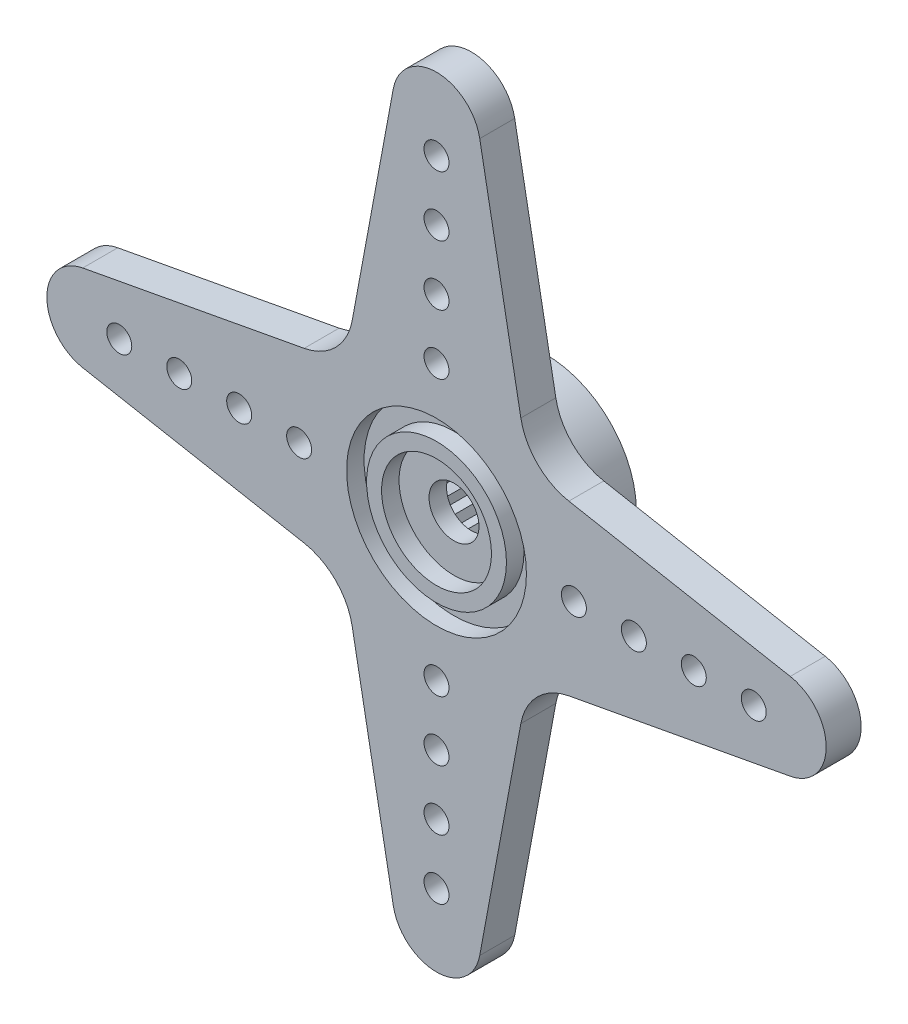
SolidWorks part; units mm, degrees
ref_plane "Front Plane" through (0, 0, 0) normal (0, 0, 1) x (1, 0, 0)
ref_plane "Top Plane" through (0, 0, 0) normal (0, 1, 0) x (1, 0, 0)
ref_plane "Right Plane" through (0, 0, 0) normal (1, 0, 0) x (0, 0, -1)
sketch "Sketch1" plane through (0, 0, 0) normal (0, 0, 1) x (1, 0, 0)
  line L50 (-10.25, 3) -> (-10.5946, 2.7283)
  line L51 (-10.5946, 2.7283) -> (-10.996, 2.9057)
  line L52 (-10.996, 2.9057) -> (-11.2623, 2.5569)
  line L53 (-11.2623, 2.5569) -> (-11.6952, 2.6289)
  line L54 (-11.6952, 2.6289) -> (-11.8664, 2.2248)
  line L55 (-11.8664, 2.2248) -> (-12.3036, 2.1869)
  line L56 (-12.3036, 2.1869) -> (-12.3689, 1.7529)
  line L57 (-12.3689, 1.7529) -> (-12.7829, 1.6075)
  line L58 (-12.7829, 1.6075) -> (-12.7382, 1.1709)
  line L59 (-12.7382, 1.1709) -> (-13.1031, 0.927)
  line L60 (-13.1031, 0.927) -> (-12.9512, 0.5153)
  line L61 (-12.9512, 0.5153) -> (-13.244, 0.1884)
  line L62 (-13.244, 0.1884) -> (-12.9945, -0.1727)
  line L63 (-12.9945, -0.1727) -> (-13.1968, -0.5621)
  line L64 (-13.1968, -0.5621) -> (-12.8654, -0.8498)
  line L65 (-12.8654, -0.8498) -> (-12.9644, -1.2773)
  line L66 (-12.9644, -1.2773) -> (-12.5719, -1.4735)
  line L67 (-12.5719, -1.4735) -> (-12.5615, -1.9123)
  line L68 (-12.5615, -1.9123) -> (-12.1325, -2.0047)
  line L69 (-12.1325, -2.0047) -> (-12.0133, -2.427)
  line L70 (-12.0133, -2.427) -> (-11.5748, -2.4098)
  line L71 (-11.5748, -2.4098) -> (-11.3543, -2.7893)
  line L72 (-11.3543, -2.7893) -> (-10.9339, -2.6636)
  line L73 (-10.9339, -2.6636) -> (-10.626, -2.9763)
  line L74 (-10.626, -2.9763) -> (-10.25, -2.75)
  line L75 (-10.25, -2.75) -> (-9.874, -2.9763)
  line L76 (-9.874, -2.9763) -> (-9.5661, -2.6636)
  line L77 (-9.5661, -2.6636) -> (-9.1456, -2.7893)
  line L78 (-9.1456, -2.7893) -> (-8.9251, -2.4098)
  line L79 (-8.9251, -2.4098) -> (-8.4866, -2.427)
  line L80 (-8.4866, -2.427) -> (-8.3675, -2.0047)
  line L81 (-8.3675, -2.0047) -> (-7.9384, -1.9123)
  line L82 (-7.9384, -1.9123) -> (-7.9281, -1.4735)
  line L83 (-7.9281, -1.4735) -> (-7.5355, -1.2773)
  line L84 (-7.5355, -1.2773) -> (-7.6346, -0.8498)
  line L85 (-7.6346, -0.8498) -> (-7.3031, -0.5621)
  line L86 (-7.3031, -0.5621) -> (-7.5054, -0.1727)
  line L87 (-7.5054, -0.1727) -> (-7.2559, 0.1884)
  line L88 (-7.2559, 0.1884) -> (-7.5487, 0.5153)
  line L89 (-7.5487, 0.5153) -> (-7.3968, 0.927)
  line L90 (-7.3968, 0.927) -> (-7.7617, 1.1709)
  line L91 (-7.7617, 1.1709) -> (-7.717, 1.6075)
  line L92 (-7.717, 1.6075) -> (-8.1311, 1.7529)
  line L93 (-8.1311, 1.7529) -> (-8.1963, 2.1869)
  line L94 (-8.1963, 2.1869) -> (-8.6336, 2.2248)
  line L95 (-8.6336, 2.2248) -> (-8.8047, 2.6289)
  line L96 (-8.8047, 2.6289) -> (-9.2376, 2.5569)
  line L97 (-9.2376, 2.5569) -> (-9.5039, 2.9057)
  line L98 (-9.5039, 2.9057) -> (-9.9053, 2.7283)
  line L99 (-9.9053, 2.7283) -> (-10.25, 3)
  line L100 (-10.25, 3) -> (-10.5946, 2.7283)
  line L101 (-10.5946, 2.7283) -> (-10.996, 2.9057)
  line L102 (-10.996, 2.9057) -> (-11.2623, 2.5569)
  line L103 (-11.2623, 2.5569) -> (-11.6952, 2.6289)
  line L104 (-11.6952, 2.6289) -> (-11.8664, 2.2248)
  line L105 (-11.8664, 2.2248) -> (-12.3036, 2.1869)
  line L106 (-12.3036, 2.1869) -> (-12.3689, 1.7529)
  line L107 (-12.3689, 1.7529) -> (-12.7829, 1.6075)
  line L108 (-12.7829, 1.6075) -> (-12.7382, 1.1709)
  line L109 (-12.7382, 1.1709) -> (-13.1031, 0.927)
  line L110 (-13.1031, 0.927) -> (-12.9512, 0.5153)
  line L111 (-12.9512, 0.5153) -> (-13.244, 0.1884)
  line L112 (-13.244, 0.1884) -> (-12.9945, -0.1727)
  line L113 (-12.9945, -0.1727) -> (-13.1968, -0.5621)
  line L114 (-13.1968, -0.5621) -> (-12.8654, -0.8498)
  line L115 (-12.8654, -0.8498) -> (-12.9644, -1.2773)
  line L116 (-12.9644, -1.2773) -> (-12.5719, -1.4735)
  line L117 (-12.5719, -1.4735) -> (-12.5615, -1.9123)
  line L118 (-12.5615, -1.9123) -> (-12.1325, -2.0047)
  line L119 (-12.1325, -2.0047) -> (-12.0133, -2.427)
  line L120 (-12.0133, -2.427) -> (-11.5748, -2.4098)
  line L121 (-11.5748, -2.4098) -> (-11.3543, -2.7893)
  line L122 (-11.3543, -2.7893) -> (-10.9339, -2.6636)
  line L123 (-10.9339, -2.6636) -> (-10.626, -2.9763)
  line L124 (-10.626, -2.9763) -> (-10.25, -2.75)
  line L125 (-10.25, -2.75) -> (-9.874, -2.9763)
  line L126 (-9.874, -2.9763) -> (-9.5661, -2.6636)
  line L127 (-9.5661, -2.6636) -> (-9.1456, -2.7893)
  line L128 (-9.1456, -2.7893) -> (-8.9251, -2.4098)
  line L129 (-8.9251, -2.4098) -> (-8.4866, -2.427)
  line L130 (-8.4866, -2.427) -> (-8.3675, -2.0047)
  line L131 (-8.3675, -2.0047) -> (-7.9384, -1.9123)
  line L132 (-7.9384, -1.9123) -> (-7.9281, -1.4735)
  line L133 (-7.9281, -1.4735) -> (-7.5355, -1.2773)
  line L134 (-7.5355, -1.2773) -> (-7.6346, -0.8498)
  line L135 (-7.6346, -0.8498) -> (-7.3031, -0.5621)
  line L136 (-7.3031, -0.5621) -> (-7.5054, -0.1727)
  line L137 (-7.5054, -0.1727) -> (-7.2559, 0.1884)
  line L138 (-7.2559, 0.1884) -> (-7.5487, 0.5153)
  line L139 (-7.5487, 0.5153) -> (-7.3968, 0.927)
  line L140 (-7.3968, 0.927) -> (-7.7617, 1.1709)
  line L141 (-7.7617, 1.1709) -> (-7.717, 1.6075)
  line L142 (-7.717, 1.6075) -> (-8.1311, 1.7529)
  line L143 (-8.1311, 1.7529) -> (-8.1963, 2.1869)
  line L144 (-8.1963, 2.1869) -> (-8.6336, 2.2248)
  line L145 (-8.6336, 2.2248) -> (-8.8047, 2.6289)
  line L146 (-8.8047, 2.6289) -> (-9.2376, 2.5569)
  line L147 (-9.2376, 2.5569) -> (-9.5039, 2.9057)
  line L148 (-9.5039, 2.9057) -> (-9.9053, 2.7283)
  line L149 (-9.9053, 2.7283) -> (-10.25, 3)
  circle A0 centre (-10.25, 0) radius 4.5
  dimension "D2" = 9
  dimension "D1" = 0
extrude "Boss-Extrude1" add sketch "Sketch1" against normal blind 3.75 contours A0 L149 L148 L147 L146 L145 L144 L143 L142 L141 L140 L139 L138 L137 L136 L135 L134 L133 L132 L131 L130 L129 L128 L127 L126 L125 L124 L123 L122 L121 L120 L119 L118 L117 L116 L115 L114 L113 L112 L111 L110 L109 L108 L107 L106 L105 L104 L103 L102 L101
sketch "Sketch2" plane through (0, 0, 0) normal (0, 0, 1) x (1, 0, 0)
  circle A0 centre (-10.25, 0) radius 1.25
  circle A1 centre (-10.25, 0) radius 3.5
  circle A2 centre (-10.25, 0) radius 4.5
  dimension "D1" = 7
  dimension "D2" = 2.5
  dimension "D3" = 9
extrude "Boss-Extrude2" add sketch "Sketch2" along normal blind 1.75 contours A2 A1 | A1 A0
sketch "Sketch4" plane through (0, 0, 1.75) normal (0, 0, 1) x (1, 0, 0)
  circle A0 centre (-10.25, 0) radius 3.5
  circle A1 centre (-10.25, 0) radius 2.75
  circle M2 centre (-10.25, 0) radius 1.25
  dimension "D1" = 7
  dimension "D2" = 0.75
extrude "Cut-Extrude1" cut sketch "Sketch4" against normal blind 0.875 contours A1 M2
sketch "Sketch6" plane through (0, 0, 1.75) normal (0, 0, 1) x (1, 0, 0)
  circle A0 centre (-10.25, 0) radius 3.5
  circle A1 centre (-10.25, 0) radius 2.75 construction
  circle A2 centre (-10.25, 0) radius 4.5
  circle M2 centre (-10.25, 0) radius 4.5
  dimension "D1" = 0.75
  dimension "D2" = 9
extrude "Cut-Extrude2" cut sketch "Sketch6" against normal blind 0.875 contours A0 M2
sketch "Sketch7" [suppressed] plane through (0, 0, 1.75) normal (0, 0, 1) x (1, 0, 0)
  circle A0 centre (-10.25, 0) radius 10.5
  circle A1 centre (-10.25, 0) radius 4.5
  dimension "D1" = 21
extrude "Boss-Extrude3" [suppressed] add sketch "Sketch7" against normal blind 1.75
sketch "Sketch9" [suppressed] plane through (0, 0, 1.75) normal (0, 0, 1) x (1, 0, 0)
  line L0 (-10.25, 0) -> (-10.25, 11.6833) construction
  circle A0 centre (-10.25, 7.875) radius 0.625
  circle A1 centre (-14.125, 7.875) radius 0.625
  circle A2 centre (-10.25, 0) radius 10.5 construction
  circle A3 centre (-6.375, 7.875) radius 0.625
  dimension "D1" = 2
  dimension "D2" = 1.25
  dimension "D3" = 1.25
  dimension "D4" = 2.625
extrude "Cut-Extrude3" [suppressed] cut sketch "Sketch9" against normal through all
pattern_circular "CirPattern1" [suppressed] count 4 over 360
chamfer "Chamfer1" [suppressed] distance 1 angle 30
sketch "Sketch10" plane through (0, 0, 1.75) normal (0, 0, 1) x (1, 0, 0)
  line L0 (-10.25, 0) -> (-10.25, 9.0053) construction
  line L1 (-10.25, 0) -> (0.0732, 10.3232) construction
  line L2 (-10.25, 0) -> (1.1009, 0) construction
  line L3 (-8.0869, 17.7016) -> (-6.0299, 6.622)
  line L4 (-3.6279, 4.2201) -> (7.4516, 2.163)
  line L5 (7.4516, -2.163) -> (-3.6279, -4.2201)
  line L6 (-6.0299, -6.622) -> (-8.0869, -17.7016)
  line L7 (-12.413, -17.7016) -> (-14.47, -6.622)
  line L8 (-16.872, -4.2201) -> (-27.9515, -2.163)
  line L9 (-27.9515, 2.163) -> (-16.872, 4.2201)
  line L10 (-14.47, 6.622) -> (-12.413, 17.7016)
  arc A0 (-8.0869, 17.7016) -> (-10.25, 19.5) centre (-10.25, 17.3) ccw
  arc A1 (7.4516, -2.163) -> (7.4516, 2.163) centre (7.05, 0) ccw
  arc A2 (-6.0299, 6.622) -> (-3.6279, 4.2201) centre (-3.0803, 7.1697) ccw
  circle A3 centre (-10.25, 15.875) radius 0.625
  circle A4 centre (-10.25, 12.875) radius 0.625
  circle A5 centre (-10.25, 9.875) radius 0.625
  circle A6 centre (-10.25, 6.875) radius 0.625
  arc A7 (7.4516, -2.163) -> (9.25, 0) centre (7.05, 0) ccw
  circle A8 centre (5.625, 0) radius 0.625
  circle A9 centre (2.625, 0) radius 0.625
  circle A10 centre (-0.375, 0) radius 0.625
  circle A11 centre (-3.375, 0) radius 0.625
  arc A12 (-3.6279, -4.2201) -> (-6.0299, -6.622) centre (-3.0803, -7.1697) ccw
  arc A13 (-12.413, -17.7016) -> (-8.0869, -17.7016) centre (-10.25, -17.3) ccw
  arc A14 (-12.413, -17.7016) -> (-10.25, -19.5) centre (-10.25, -17.3) ccw
  circle A15 centre (-10.25, -15.875) radius 0.625
  circle A16 centre (-10.25, -12.875) radius 0.625
  circle A17 centre (-10.25, -9.875) radius 0.625
  circle A18 centre (-10.25, -6.875) radius 0.625
  arc A19 (-14.47, -6.622) -> (-16.872, -4.2201) centre (-17.4196, -7.1697) ccw
  arc A20 (-27.9515, 2.163) -> (-27.9515, -2.163) centre (-27.5499, 0) ccw
  arc A21 (-27.9515, 2.163) -> (-29.7499, 0) centre (-27.5499, 0) ccw
  circle A22 centre (-26.1249, 0) radius 0.625
  circle A23 centre (-23.1249, 0) radius 0.625
  circle A24 centre (-20.1249, 0) radius 0.625
  circle A25 centre (-17.1249, 0) radius 0.625
  arc A26 (-16.872, 4.2201) -> (-14.47, 6.622) centre (-17.4196, 7.1697) ccw
  arc A27 (-8.0869, 17.7016) -> (-12.413, 17.7016) centre (-10.25, 17.3) ccw
  circle A28 centre (-10.25, 0) radius 4.5
  point P1 (-10.25, 0)
  point P10 (-5.6538, 4.5962)
  point P20 (-5.6538, 4.5962)
  point P21 (-10.25, 19.5)
  point P84 (-10.25, 0)
  circle M4 centre (-10.25, 0) radius 3.5
  dimension "D2" = 19.5
  dimension "D3" = 19.5
  dimension "D4" = 4.4
  dimension "D5" = 4.4
  dimension "D7" = 3
  dimension "D8" = 1.25
  dimension "D9" = 3
  dimension "D1" = 45
  dimension "D6" = 6.5
  dimension "D10" = 4
  dimension "D11" = 4
extrude "Boss-Extrude4" add sketch "Sketch10" against normal blind 1.75 contours A0 A27 L10 A26 L9 A20 L8 A19 L7 A13 L6 A12 L5 A1 L4 A2 L3 A3 A4 A5 A6 A8 A9 A10 A11 A15 A16 A17 A18 A22 A23 M4
chamfer "Chamfer2" distance 1 angle 30 1 edges at (-5.75, 0, 0)
sketch "Sketch11" [suppressed] plane through (0, 0, 1.75) normal (0, 0, 1) x (1, 0, 0)
  line L0 (-10.25, 0) -> (-10.25, 17.5605) construction
  line L1 (-10.25, 0) -> (4.9579, 8.7803) construction
  line L2 (-10.25, 0) -> (4.9579, -8.7803) construction
  line L3 (-10.25, 0) -> (-10.25, -17.5605) construction
  line L4 (-10.25, 0) -> (-25.4578, -8.7803) construction
  line L5 (-10.25, 0) -> (-25.4578, 8.7803) construction
  line L6 (-10.25, 0) -> (-3.969, 10.8789) construction
  line L7 (-10.25, 0) -> (2.312, 0) construction
  line L8 (-10.25, 0) -> (-3.969, -10.8789) construction
  line L9 (-10.25, 0) -> (-16.5309, -10.8789) construction
  line L10 (-10.25, 0) -> (-22.8119, 0) construction
  line L11 (-10.25, 0) -> (-16.5309, 10.8789) construction
  line L12 (-8.5769, 14.5133) -> (-6.25, 6.9282)
  line L13 (-6.25, 6.9282) -> (1.4824, 8.7055)
  line L14 (3.1554, 5.8077) -> (-2.25, 0)
  line L15 (-2.25, 0) -> (3.1554, -5.8077)
  line L16 (1.4824, -8.7055) -> (-6.25, -6.9282)
  line L17 (-6.25, -6.9282) -> (-8.5769, -14.5133)
  line L18 (-11.923, -14.5133) -> (-14.25, -6.9282)
  line L19 (-14.25, -6.9282) -> (-21.9823, -8.7055)
  line L20 (-23.6553, -5.8077) -> (-18.25, 0)
  line L21 (-18.25, 0) -> (-23.6553, 5.8077)
  line L22 (-21.9823, 8.7055) -> (-14.25, 6.9282)
  line L23 (-14.25, 6.9282) -> (-11.923, 14.5133)
  circle A0 centre (-10.25, 0) radius 4.5
  arc A1 (-8.5769, 14.5133) -> (-10.25, 15.75) centre (-10.25, 14) ccw
  arc A2 (3.3899, 7.875) -> (1.4824, 8.7055) centre (1.8744, 7) ccw
  circle A4 centre (-10.25, 13.375) radius 0.625
  circle A5 centre (-10.25, 10.375) radius 0.625
  circle A6 centre (-10.25, 7.375) radius 0.625
  circle A7 centre (1.3331, 6.6875) radius 0.625
  arc A8 (3.1554, 5.8077) -> (3.3899, 7.875) centre (1.8744, 7) ccw
  circle A9 centre (-1.2649, 5.1875) radius 0.625
  circle A10 centre (-3.863, 3.6875) radius 0.625
  arc A11 (3.3899, -7.875) -> (3.1554, -5.8077) centre (1.8744, -7) ccw
  circle A12 centre (1.3331, -6.6875) radius 0.625
  arc A13 (1.4824, -8.7055) -> (3.3899, -7.875) centre (1.8744, -7) ccw
  circle A14 centre (-1.2649, -5.1875) radius 0.625
  circle A15 centre (-3.863, -3.6875) radius 0.625
  arc A16 (-10.25, -15.75) -> (-8.5769, -14.5133) centre (-10.25, -14) ccw
  circle A17 centre (-10.25, -13.375) radius 0.625
  arc A18 (-11.923, -14.5133) -> (-10.25, -15.75) centre (-10.25, -14) ccw
  circle A19 centre (-10.25, -10.375) radius 0.625
  circle A20 centre (-10.25, -7.375) radius 0.625
  arc A21 (-23.8899, -7.875) -> (-21.9823, -8.7055) centre (-22.3743, -7) ccw
  circle A22 centre (-21.833, -6.6875) radius 0.625
  arc A23 (-23.6553, -5.8077) -> (-23.8899, -7.875) centre (-22.3743, -7) ccw
  circle A24 centre (-19.235, -5.1875) radius 0.625
  circle A25 centre (-16.6369, -3.6875) radius 0.625
  arc A26 (-23.8899, 7.875) -> (-23.6553, 5.8077) centre (-22.3743, 7) ccw
  circle A27 centre (-21.833, 6.6875) radius 0.625
  arc A28 (-21.9823, 8.7055) -> (-23.8899, 7.875) centre (-22.3743, 7) ccw
  circle A29 centre (-19.235, 5.1875) radius 0.625
  circle A30 centre (-16.6369, 3.6875) radius 0.625
  arc A31 (-10.25, 15.75) -> (-11.923, 14.5133) centre (-10.25, 14) ccw
  point P5 (-10.25, 0)
  point P12 (-10.25, 0)
  point P20 (-10.25, 0)
  point P22 (-6.25, 6.9282)
  point P26 (-10.25, 15.75)
  point P27 (3.3899, 7.875)
  point P102 (-10.25, 0)
  dimension "D4" = 15.75
  dimension "D5" = 15.75
  dimension "D6" = 3.5
  dimension "D7" = 3.5
  dimension "D9" = 1.25
  dimension "D10" = 1.75
  dimension "D2" = 30
  dimension "D8" = 8
  dimension "D11" = 3
  dimension "D1" = 6
  dimension "D3" = 6
  dimension "D12" = 6
extrude "Boss-Extrude5" [suppressed] add sketch "Sketch11" against normal blind 1.75 contours A1 A31 L23 L22 A28 A26 L21 L20 A23 A21 L19 L18 A18 A16 L17 L16 A13 A11 L15 L14 A8 A2 L13 L12 A0 A4 A5 A6 A7 A9 A10 A12 A14 A15 A17 A19 A20
chamfer "Chamfer4" [suppressed] distance 1 angle 30
sketch "Sketch12" [suppressed] plane through (0, 0, 0.875) normal (0, 0, 1) x (1, 0, 0)
  circle A0 centre (-10.25, 0) radius 1.25
  circle A1 centre (-10.25, 0) radius 5
extrude "Boss-Extrude6" [suppressed] add sketch "Sketch12" along normal blind 0.125
sketch "Sketch14" [suppressed] plane through (0, 0, 1) normal (0, 0, 1) x (1, 0, 0)
  line L0 (-10.25, 0) -> (-28.2499, 0) construction
  line L1 (-10.25, -6) -> (-28.2499, -6)
  line L2 (-10.25, 6) -> (-28.2499, 6)
  arc A0 (-10.25, -6) -> (-10.25, 6) centre (-10.25, 0) ccw
  arc A1 (-28.2499, 6) -> (-28.2499, -6) centre (-28.2499, 0) ccw
  point P4 (-19.2499, 0)
  dimension "D1" = 12
  dimension "D2" = 29.9999
extrude "Boss-Extrude7" [suppressed] add sketch "Sketch14" along normal blind 3
sketch "Sketch16" [suppressed] plane through (0, 0, 1) normal (0, 0, -1) x (-1, 0, 0)
  line L0 (25.9999, 0) -> (30.4999, 0) construction
  line L1 (25.9999, 2.75) -> (30.4999, 2.75)
  line L2 (25.9999, -2.75) -> (30.4999, -2.75)
  arc A0 (25.9999, 2.75) -> (25.9999, -2.75) centre (25.9999, 0) ccw
  arc A1 (30.4999, -2.75) -> (30.4999, 2.75) centre (30.4999, 0) ccw
  arc A10 (28.2499, -6) -> (28.2499, 6) centre (28.2499, 0) ccw construction
  point P3 (28.2499, 0)
  point P8 (34.2499, 0)
  point P9 (33.2499, 0)
  dimension "D2" = 10
  dimension "D3" = 1
  dimension "D1" = 5.5
extrude "Boss-Extrude8" [suppressed] add sketch "Sketch16" along normal blind 2.75 contours L1 A1 L2 A0
sketch "Sketch17" [suppressed] plane through (0, 0, -1.75) normal (0, 0, -1) x (-1, 0, 0)
  circle A0 centre (30.7499, 0) radius 1.5
  circle A1 centre (25.7499, 0) radius 1.5
  arc A5 (28.2499, -6) -> (28.2499, 6) centre (28.2499, 0) ccw construction
  dimension "D1" = 3
  dimension "D2" = 3
  dimension "D3" = 2
  dimension "D4" = 2
extrude "Cut-Extrude4" [suppressed] cut sketch "Sketch17" against normal through all
sketch "Sketch18" [suppressed] plane through (0, 0, 1) normal (0, 0, -1) x (-1, 0, 0)
  circle A0 centre (10.25, 0) radius 3
  dimension "D1" = 6
extrude "Cut-Extrude5" [suppressed] cut sketch "Sketch18" against normal through all
sketch "Sketch19" [suppressed] plane through (0, 0, 1.5) normal (0, 0, 1) x (1, 0, 0)
  line L0 (-35.7499, 0) -> (15.25, 0) construction
  line L1 (-9.625, 5.9674) -> (14.1146, 3.481)
  line L2 (14.1146, -3.481) -> (-9.625, -5.9674)
  line L3 (-10.25, 0) -> (-10.25, 10.691) construction
  line L4 (-34.6145, -3.481) -> (-10.875, -5.9674)
  line L5 (-10.875, 5.9674) -> (-34.6145, 3.481)
  circle A0 centre (-10.25, 0) radius 6
  arc A1 (14.1146, -3.481) -> (14.1146, 3.481) centre (13.75, 0) ccw
  circle A2 centre (14.625, 0) radius 0.625
  circle A3 centre (11.375, 0) radius 0.625
  circle A4 centre (8.125, 0) radius 0.625
  circle A5 centre (4.875, 0) radius 0.625
  circle A6 centre (1.625, 0) radius 0.625
  circle A7 centre (-22.1249, 0) radius 0.625
  circle A8 centre (-25.3749, 0) radius 0.625
  circle A9 centre (-28.6249, 0) radius 0.625
  circle A10 centre (-31.8749, 0) radius 0.625
  circle A11 centre (-35.1249, 0) radius 0.625
  arc A12 (-34.6145, -3.481) -> (-34.6145, 3.481) centre (-34.2499, 0) cw
  point P37 (-10.25, -6)
  circle M5 centre (-10.25, 0) radius 5
  circle M6 centre (-10.25, 0) radius 1.25
  dimension "D1" = 12
  dimension "D2" = 7
  dimension "D4" = 1.25
  dimension "D5" = 2
  dimension "D3" = 27.4999
  dimension "D6" = 5
extrude "Boss-Extrude9" [suppressed] add sketch "Sketch19" along normal blind 2.5 contours A12 L4 A0 L5 A10 A8 A7 A9 A11 | A0 M5 | M5 M6 | L2 A1 L1 A0 A6 A5 A4 A3 A2
sketch "Sketch20" [suppressed] plane through (0, 0, 4) normal (0, 0, 1) x (1, 0, 0)
  arc A0 (-9.625, 5.9674) -> (-10.875, 5.9674) centre (-10.25, 0) ccw construction
  circle A1 centre (-10.25, 0) radius 4
  circle A2 centre (-10.25, 0) radius 6
  point P5 (-10.25, 4)
  point P7 (-10.25, -4)
  dimension "D1" = 2
extrude "Boss-Extrude10" [suppressed] add sketch "Sketch20" along normal blind 1
sketch "Sketch21" [suppressed] plane through (0, 0, 4) normal (0, 0, 1) x (1, 0, 0)
  circle A0 centre (-10.25, 0) radius 4 construction
  circle A1 centre (-10.25, 0) radius 4
  circle A2 centre (-10.25, 0) radius 3.25
  dimension "D1" = 0.75
extrude "Boss-Extrude11" [suppressed] add sketch "Sketch21" along normal offset from surface (0.5 mm away) 0.5
sketch "Sketch22" [suppressed] plane through (0, 0, 4) normal (0, 0, 1) x (1, 0, 0)
  circle A0 centre (-10.25, 0) radius 3.25
extrude "Cut-Extrude6" [suppressed] cut sketch "Sketch22" against normal offset from surface (3 mm away) 1 contours A0
chamfer "Chamfer5" [suppressed] distance 0.75 angle 45
ref_plane "Plane1" [suppressed] through (0, 4.5, 0) normal (0, 1, 0) x (1, 0, 0)
ref_plane "Plane3" [suppressed] through (0, 0.5, 0) normal (0, 1, 0) x (1, 0, 0)
sketch "Sketch26" [suppressed] plane through (0, 0.5, 0) normal (0, 1, 0) x (1, 0, 0)
  line L0 (-17.4408, -4) -> (-16.1908, -5)
  line L1 (-10.875, -4) -> (-34.6145, -4) construction
  line L2 (-16.1908, -5) -> (-15.6228, -4)
  line L3 (-15.6228, -4) -> (-17.4408, -4)
  line L4 (-16.25, -5) -> (-4.25, -5) construction
  dimension "D1" = 1.25
extrude "Boss-Extrude15" [suppressed] add sketch "Sketch26" against normal blind 1
ref_plane "Plane4" [suppressed] through (0, 5, 0) normal (0, 1, 0) x (1, 0, 0)
sketch "Sketch27" [suppressed] plane through (0, 5, 0) normal (0, 1, 0) x (1, 0, 0)
  line L0 (-17.4408, -4) -> (-13.2508, -4)
  line L1 (-16.1908, -5) -> (-13.2508, -5)
  line L3 (-17.4408, -4) -> (-16.1908, -5)
  line L4 (-16.1908, -5) -> (-15.6228, -4)
  line L5 (-15.6228, -4) -> (-17.4408, -4)
  line L6 (-17.4408, -4) -> (-16.1908, -5)
  line L10 (-13.2508, -5) -> (-13.2508, -4)
  dimension "D1" = 0
extrude "Boss-Extrude16" [suppressed] add sketch "Sketch27" against normal blind 1 contours L6 L1 L10 L0
mirror "Mirror1" [suppressed] about plane through (0, 0, 0) normal (0, 1, 0)
ref_plane "Plane5" [suppressed] through (-10.25, 0, 0) normal (1, 0, 0) x (0, 0, -1)
mirror "Mirror2" [suppressed] about plane through (-10.25, 0, 0) normal (1, 0, 0)
ref_plane "Plane6" [suppressed] through (0, 0, 2.75) normal (0, 0, 1) x (1, 0, 0)
mirror "Mirror3" [suppressed] about plane through (0, 0, 2.75) normal (0, 0, 1)
mirror "Mirror4" [suppressed] about plane through (-10.25, 0, 0) normal (1, 0, 0)
sketch "Sketch29" [suppressed] plane through (0, -5, 0) normal (0, -1, 0) x (1, 0, 0)
  line L0 (-15.25, 1.5) -> (-5.25, 1.5) construction
  line L1 (-13.2508, 0.5) -> (-7.2491, 0.5)
  line L2 (-13.2508, 0.5) -> (-13.2508, 1.5)
  line L3 (-13.2508, 1.5) -> (-7.2491, 1.5)
  line L4 (-7.2491, 0.5) -> (-7.2491, 1.5)
  line L5 (-7.2491, 0.5) -> (-7.2491, 1.5) construction
extrude "Boss-Extrude17" [suppressed] add sketch "Sketch29" against normal up to surface (1 mm away)
sketch "Sketch31" [suppressed] plane through (0, 0, 5) normal (0, 0, 1) x (1, 0, 0)
  line L1 (-19.5679, -7.6233) -> (-0.9321, -7.6233)
  line L2 (-19.5679, -7.6233) -> (-19.5679, 7.6233)
  line L3 (-19.5679, 7.6233) -> (-0.9321, 7.6233)
  line L4 (-0.9321, -7.6233) -> (-0.9321, 7.6233)
  line L5 (-19.5679, -7.6233) -> (-0.9321, 7.6233) construction
  line L6 (-19.5679, 7.6233) -> (-0.9321, -7.6233) construction
  point P0 (-10.25, 0)
  point P1 (-10.25, 0)
extrude "Cut-Extrude7" [suppressed] cut sketch "Sketch31" against normal blind 0.7493
ref_plane "Plane7" through (-10.25, 0, 0) normal (1, 0, 0) x (0, 0, -1)
